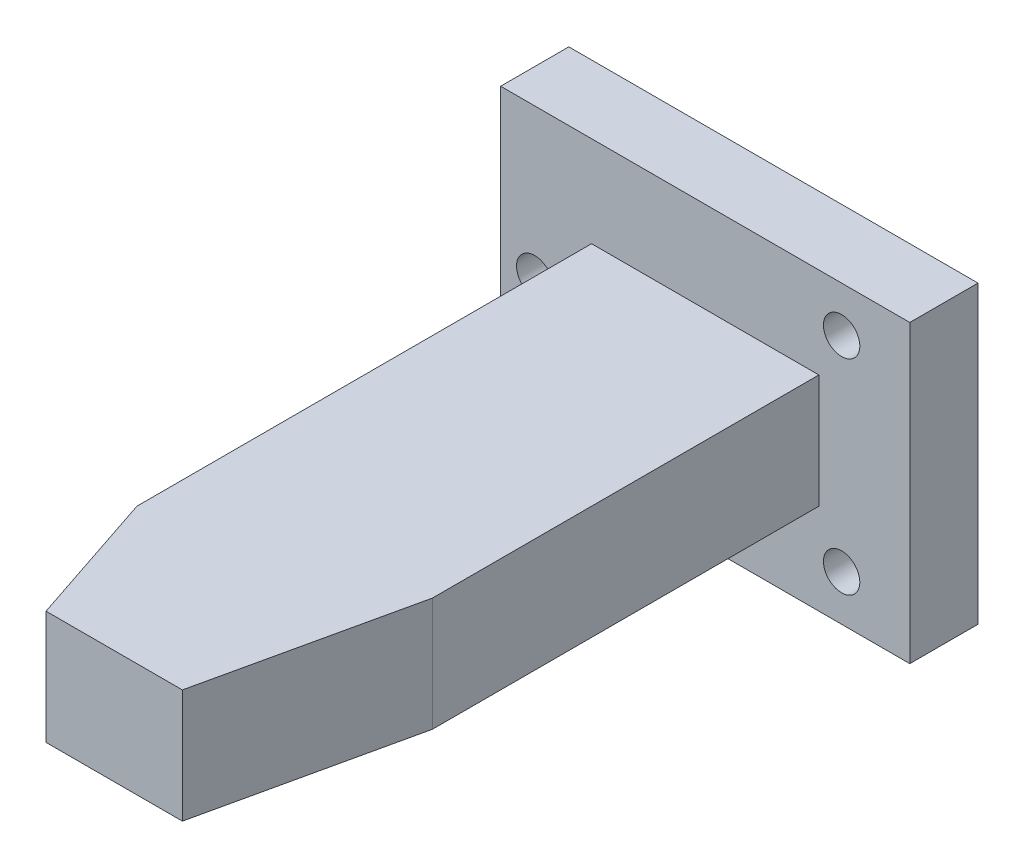
SolidWorks part; units mm, degrees
ref_plane "前视基准面" through (0, 0, 0) normal (0, 0, 1) x (1, 0, 0)
ref_plane "上视基准面" through (0, 0, 0) normal (0, 1, 0) x (1, 0, 0)
ref_plane "右视基准面" through (0, 0, 0) normal (1, 0, 0) x (0, 0, -1)
other "Configuration Table"
sketch "草图1" plane through (0, 0, 0) normal (0, 0, 1) x (1, 0, 0)
  line L0 (0, -13) -> (36, -13)
  line L1 (36, -13) -> (36, 13)
  line L2 (36, 13) -> (0, 13)
  line L3 (0, 13) -> (0, -13)
extrude "凸台-拉伸1" add sketch "草图1" along normal blind 6
sketch "草图2" plane through (0, 0, 0) normal (0, 1, 0) x (1, 0, 0)
  line L0 (8, -6) -> (28, -6)
  line L1 (36, -6) -> (0, -6) construction
  line L2 (28, -6) -> (28, -40)
  line L3 (28, -40) -> (24, -58)
  line L4 (24, -58) -> (12, -58)
  line L5 (12, -58) -> (8, -46)
  line L6 (8, -46) -> (8, -6)
extrude "凸台-拉伸2" add sketch "草图2" along normal blind 10 from offset 5
sketch "草图3" plane through (0, 0, 0) normal (0, 0, 1) x (1, 0, 0)
  line L0 (8, 5) -> (8, -5) construction
  circle A0 centre (8, 0) radius 1.6
  circle A1 centre (30, -9) radius 1.6
  circle A2 centre (30, 9) radius 1.6
  circle A3 centre (3, 0) radius 1.6
extrude "切除-拉伸2" cut sketch "草图3" along normal through all
sketch "草图4" plane through (0, 0, 0) normal (0, 1, 0) x (1, 0, 0)
  circle A0 centre (18, -54) radius 3
  circle A1 centre (18, -18) radius 3
  circle A2 centre (18, -36) radius 3
extrude "切除-拉伸3" cut sketch "草图4" against normal through all
